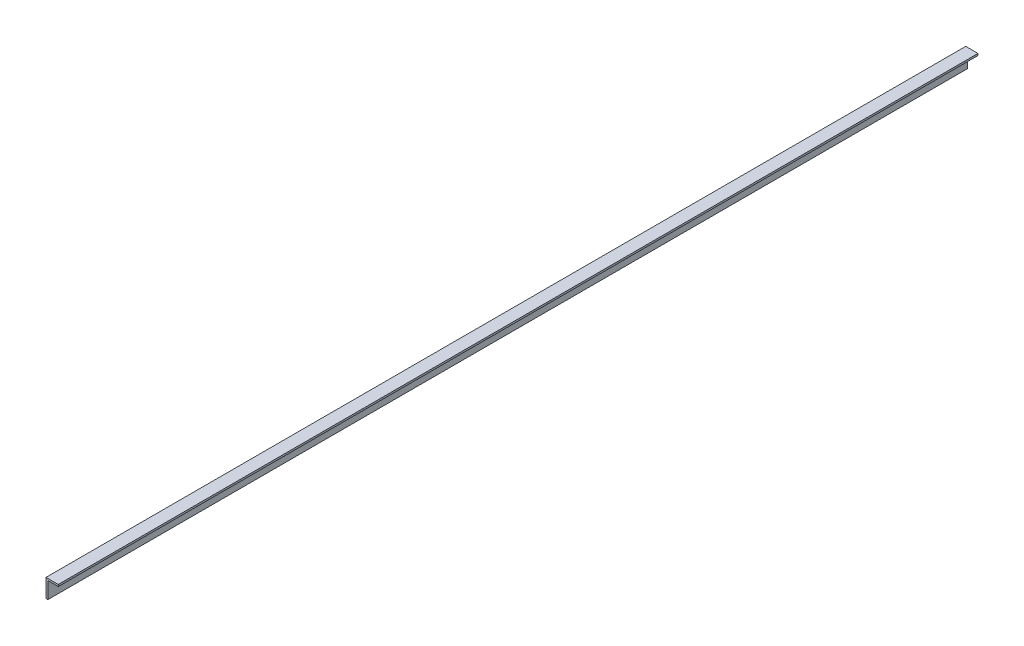
SolidWorks part; units mm, degrees
ref_plane "Front" through (0, 0, 0) normal (0, 0, 1) x (1, 0, 0)
ref_plane "Top" through (0, 0, 0) normal (0, 1, 0) x (1, 0, 0)
ref_plane "Right" through (0, 0, 0) normal (1, 0, 0) x (0, 0, -1)
sketch "Esquisse1" plane through (0, 0, 0) normal (0, 0, 1) x (1, 0, 0)
  line L0 (0, 0) -> (0, 30)
  line L1 (0, 30) -> (20, 30)
  line L2 (20, 30) -> (20, 27)
  line L3 (20, 27) -> (3, 27)
  line L4 (3, 27) -> (3, 0)
  line L5 (3, 0) -> (0, 0)
  dimension "D1" = 30
  dimension "D2" = 20
  dimension "D3" = 3
extrude "Boss.-Extru.1" add sketch "Esquisse1" along normal blind 1500
